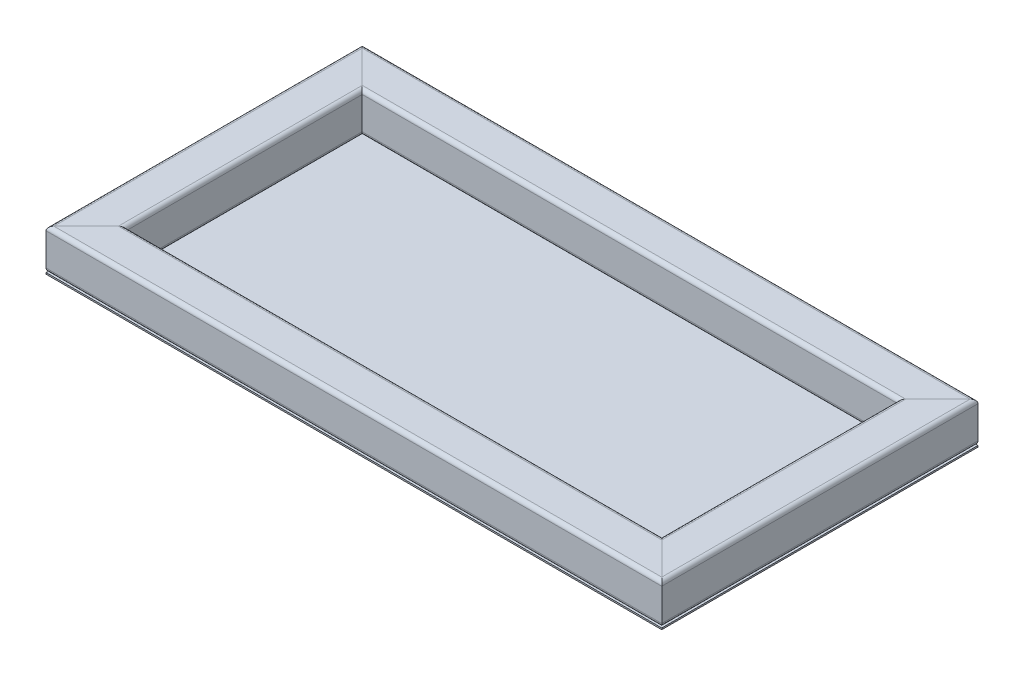
SolidWorks part; units mm, degrees
material "ASTM A36 Acero"
ref_plane "Alzado" through (0, 0, 0) normal (0, 0, 1) x (1, 0, 0)
ref_plane "Planta" through (0, 0, 0) normal (0, 1, 0) x (1, 0, 0)
ref_plane "Vista lateral" through (0, 0, 0) normal (1, 0, 0) x (0, 0, -1)
sketch "Croquis1" plane through (0, 0, 0) normal (0, 1, 0) x (1, 0, 0)
  line L1 (-390, 200.3) -> (390, 200.3)
  line L2 (-390, 200.3) -> (-390, -200.3)
  line L3 (-390, -200.3) -> (390, -200.3)
  line L4 (390, 200.3) -> (390, -200.3)
  line L5 (-390, 200.3) -> (390, -200.3) construction
  line L6 (-390, -200.3) -> (390, 200.3) construction
  point P0 (0, 0)
  dimension "D1" = 400.6
  dimension "D2" = 780
other "Tubo cuadrado 2 X 2 X 0.25(1)"
ref_plane "Plano1" through (-364.6, 25.4, -200.3) normal (0, 0, 1) x (1, 0, 0)
sketch "Sketch1" plane through (-364.6, 25.4, -200.3) normal (0, 0, 1) x (1, 0, 0)
  line L0 (-20.4, -23.4) -> (20.4, -23.4)
  line L1 (-23.4, -20.4) -> (-23.4, 20.4)
  line L2 (20.4, 23.4) -> (-20.4, 23.4)
  line L3 (23.4, 20.4) -> (23.4, -20.4)
  line L4 (-20.4, -25.4) -> (20.4, -25.4)
  line L5 (-25.4, -20.4) -> (-25.4, 20.4)
  line L6 (20.4, 25.4) -> (-20.4, 25.4)
  line L7 (25.4, 20.4) -> (25.4, -20.4)
  line L8 (0, 0) -> (23.4, 0) construction
  line L9 (0, 0) -> (0, 23.4) construction
  arc A0 (25.4, 20.4) -> (20.4, 25.4) centre (20.4, 20.4) ccw
  arc A1 (20.4, -25.4) -> (25.4, -20.4) centre (20.4, -20.4) ccw
  arc A2 (-25.4, -20.4) -> (-20.4, -25.4) centre (-20.4, -20.4) ccw
  arc A3 (-20.4, 25.4) -> (-25.4, 20.4) centre (-20.4, 20.4) ccw
  arc A4 (-20.4, 23.4) -> (-23.4, 20.4) centre (-20.4, 20.4) ccw
  arc A5 (23.4, 20.4) -> (20.4, 23.4) centre (20.4, 20.4) ccw
  arc A6 (20.4, -23.4) -> (23.4, -20.4) centre (20.4, -20.4) ccw
  arc A7 (-23.4, -20.4) -> (-20.4, -23.4) centre (-20.4, -20.4) ccw
  point P3 (0, 25.4)
  point P4 (25.4, 0)
  point P5 (0, -25.4)
  point P6 (-25.4, 0)
  point P7 (-25.4, 25.4)
  point P8 (-25.4, -25.4)
  point P33 (0, 0)
  point P35 (25.4, -25.4)
  point P36 (25.4, 25.4)
  point P37 (0, 0)
  dimension "D1" = 5
  dimension "Thickness" = 2
  dimension "V_leg" = 50.8
sketch "Croquis3" plane through (0, 0, 0) normal (0, -1, 0) x (1, 0, 0)
  line L0 (390, -200.3) -> (385, -195.3) construction
  line L1 (-390, 200.3) -> (390, 200.3)
  line L2 (-390, 200.3) -> (-390, -200.3)
  line L3 (-390, -200.3) -> (390, -200.3)
  line L4 (390, 200.3) -> (390, -200.3)
  line L5 (-390, 200.3) -> (390, -200.3) construction
  line L6 (-390, -200.3) -> (390, 200.3) construction
  line L7 (-390, -200.3) -> (390, -200.3) construction
  point P0 (0, 0)
extrude "Saliente-Extruir1" add sketch "Croquis3" along normal blind 1.9 separate body
